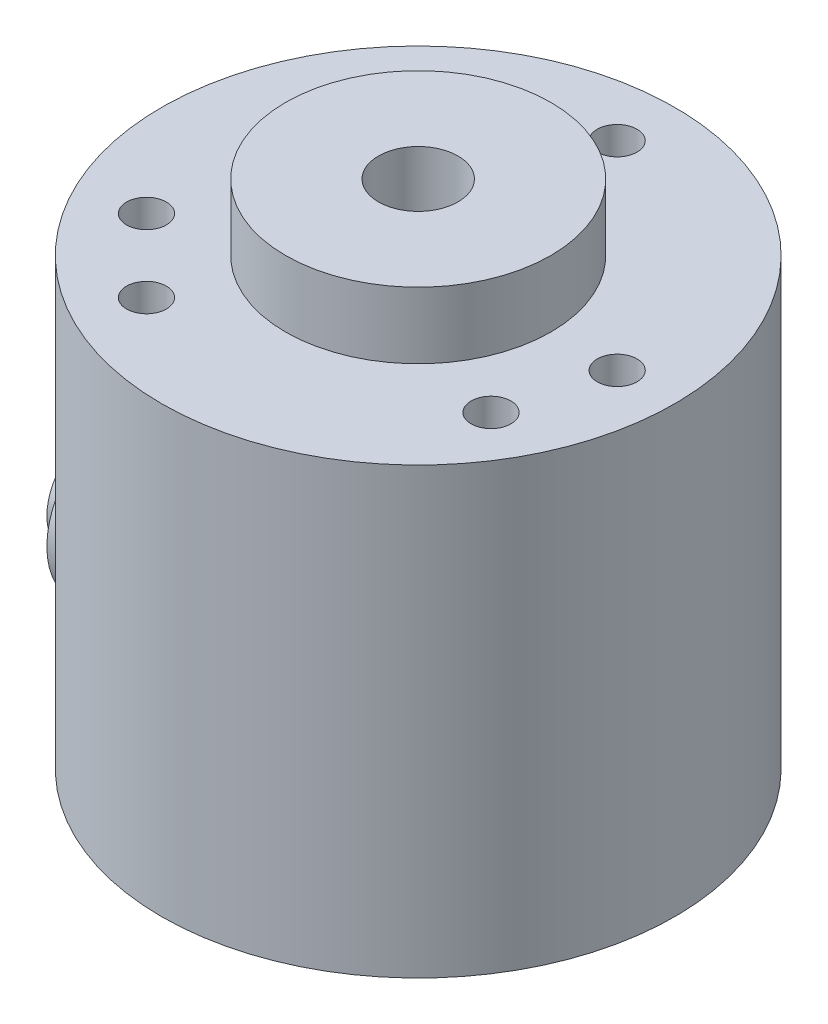
SolidWorks part; units mm, degrees
ref_plane "Front Plane" through (0, 0, 0) normal (0, 0, 1) x (1, 0, 0)
ref_plane "Top Plane" through (0, 0, 0) normal (0, 1, 0) x (1, 0, 0)
ref_plane "Right Plane" through (0, 0, 0) normal (1, 0, 0) x (0, 0, -1)
sketch "Sketch2" plane through (0, 0, 0) normal (0, 1, 0) x (1, 0, 0)
  circle A0 centre (0, 0) radius 19.35
  dimension "D1" = 38.7
extrude "Boss-Extrude1" add sketch "Sketch2" along normal blind 33.5
sketch "Sketch3" plane through (0, 33.5, 0) normal (0, 1, 0) x (1, 0, 0)
  circle A0 centre (0, 0) radius 10
  dimension "D1" = 20
extrude "Boss-Extrude2" add sketch "Sketch3" along normal blind 5
sketch "Sketch4" plane through (0, 33.5, 0) normal (0, 1, 0) x (1, 0, 0)
  line L0 (-30.1779, 0) -> (35.0606, 0) construction
  line L1 (0, 33.3099) -> (0, -48.9541) construction
  line L2 (0, 0) -> (29.0176, -16.7533) construction
  line L3 (0, 0) -> (-27.4182, -15.8299) construction
  line L4 (0, 0) -> (-16.3166, -28.2613) construction
  line L5 (0, 0) -> (-11.5228, 19.958) construction
  circle A0 centre (15, 0) radius 1.5
  circle A1 centre (0, 0) radius 15 construction
  circle A2 centre (12.9904, -7.5) radius 1.5
  circle A3 centre (0, 15) radius 1.5
  circle A4 centre (-12.9904, -7.5) radius 1.5
  circle A5 centre (-7.5, -12.9904) radius 1.5
  circle A6 centre (-7.5, 12.9904) radius 1.5
  dimension "D1" = 3
  dimension "D2" = 30
  dimension "D3" = 3
  dimension "D5" = 3
  dimension "D7" = 3
  dimension "D10" = 3
  dimension "D11" = 3
  dimension "D4" = 30
  dimension "D6" = 30
  dimension "D8" = 30
  dimension "D9" = 30
extrude "Cut-Extrude1" cut sketch "Sketch4" against normal blind 3
sketch "Sketch5" plane through (0, 38.5, 0) normal (0, 1, 0) x (1, 0, 0)
  line L0 (-31.8733, 0) -> (32.348, 0) construction
  line L1 (0, 20.7109) -> (0, -23.7219) construction
  circle A0 centre (0, 0) radius 3
  dimension "D1" = 6
extrude "Cut-Extrude2" cut sketch "Sketch5" against normal blind 6
ref_plane "Plane1" through (-22, 0, 0) normal (1, 0, 0) x (0, 0, -1)
sketch "Sketch6" plane through (-22, 0, 0) normal (1, 0, 0) x (0, 0, -1)
  line L0 (0, 0) -> (0, 43.9892) construction
  line L1 (-19.35, 0) -> (19.35, 0) construction
  circle A0 centre (0, 6.5) radius 6
  point P5 (0, 5.3373)
  point P6 (0, 2.8931)
  dimension "D1" = 12
  dimension "D2" = 6.5
extrude "Boss-Extrude3" add sketch "Sketch6" along normal up to surface (3.6037 mm away)
sketch "Sketch7" plane through (-22, 0, 0) normal (-1, 0, 0) x (0, 0, 1)
  circle A0 centre (0, 6.5) radius 4
  dimension "D1" = 8
extrude "Boss-Extrude4" add sketch "Sketch7" along normal blind 2
